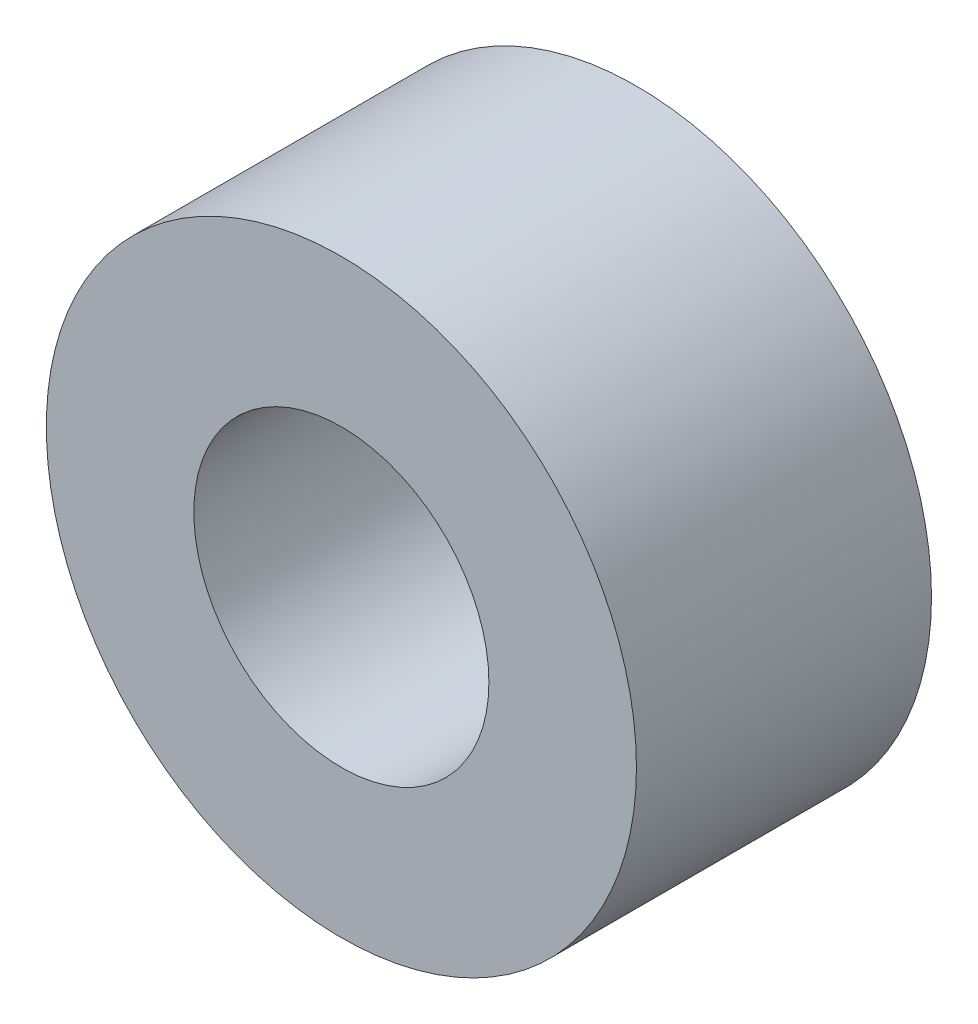
SolidWorks part; units mm, degrees
ref_plane "Front Plane" through (0, 0, 0) normal (0, 0, 1) x (1, 0, 0)
ref_plane "Top Plane" through (0, 0, 0) normal (0, 1, 0) x (1, 0, 0)
ref_plane "Right Plane" through (0, 0, 0) normal (1, 0, 0) x (0, 0, -1)
sketch "Sketch1" plane through (0, 0, 0) normal (0, 0, 1) x (1, 0, 0)
  circle A0 centre (0, 0) radius 3.175
  circle A1 centre (0, 0) radius 6.35
  dimension "D1" = 6.35
  dimension "D2" = 12.7
extrude "Boss-Extrude1" add sketch "Sketch1" along normal blind 6.35
